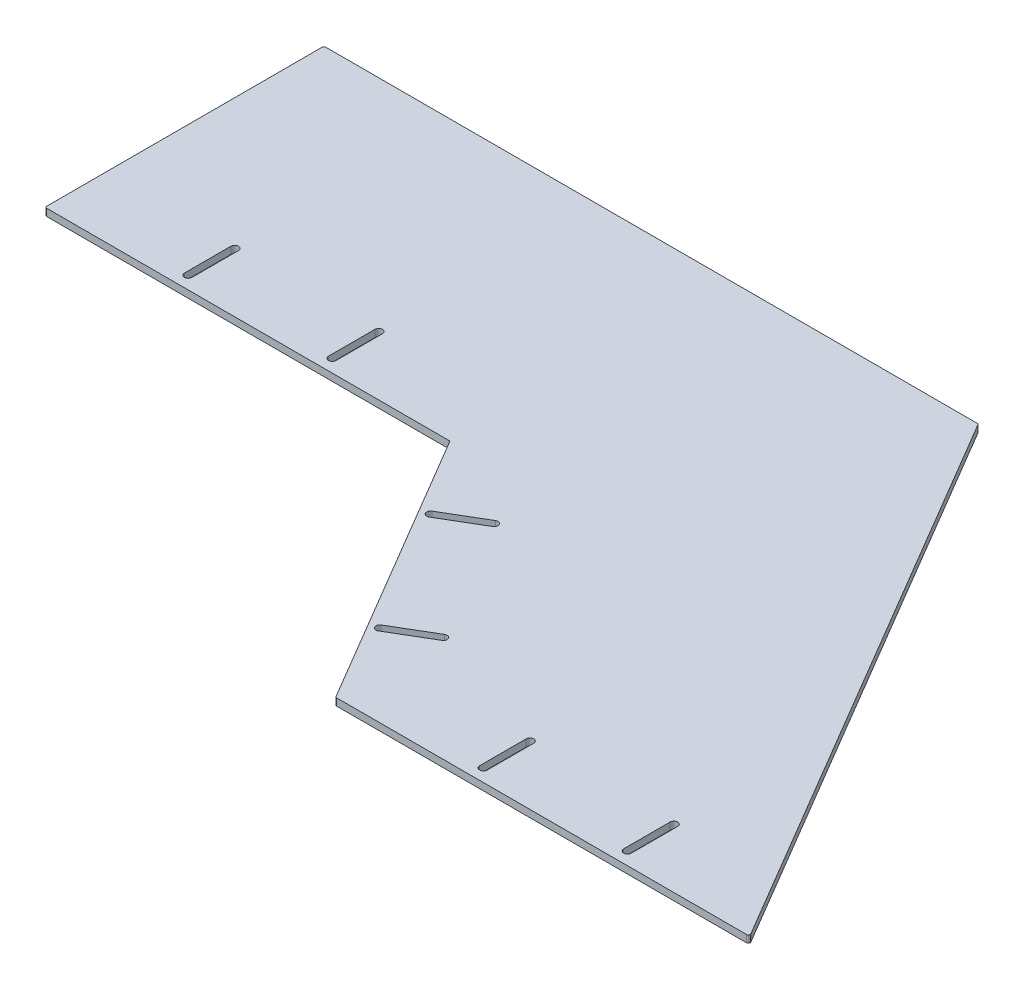
SolidWorks part; units mm, degrees
ref_plane "Front Plane" through (0, 0, 0) normal (1, 0, 0) x (0, 1, 0)
ref_plane "Top Plane" through (0, 0, 0) normal (0, 0, 1) x (0, 1, 0)
ref_plane "Right Plane" through (0, 0, 0) normal (0, 1, 0) x (-1, 0, 0)
sketch "Sketch1" plane through (0, 0, 0) normal (0, 1, 0) x (-1, 0, 0)
  line L0 (0, 0) -> (-183.0301, 310)
  line L1 (-183.0301, 310) -> (46.9699, 310)
  line L2 (46.9699, 310) -> (138.485, 155)
  line L3 (138.485, 155) -> (363.485, 155)
  line L4 (363.485, 155) -> (363.485, 0)
  line L5 (363.485, 0) -> (0, 0)
  line L6 (-108.0301, 302.9) -> (-108.0301, 277.1) construction
  line L7 (-105.9301, 302.9) -> (-105.9301, 277.1)
  line L8 (-110.1301, 302.9) -> (-110.1301, 277.1)
  line L9 (-68.0301, 310) -> (-68.0301, 296.3589) construction
  line L10 (-28.0301, 302.9) -> (-28.0301, 277.1) construction
  line L11 (-30.1301, 302.9) -> (-30.1301, 277.1)
  line L12 (-25.9301, 302.9) -> (-25.9301, 277.1)
  line L13 (45.8686, 251.2852) -> (68.0852, 264.4024) construction
  line L14 (44.8009, 253.0935) -> (67.0176, 266.2107)
  line L15 (46.9362, 249.4769) -> (69.1529, 262.594)
  line L16 (92.7275, 232.5) -> (68.0021, 217.9017) construction
  line L17 (86.5419, 182.3963) -> (108.7586, 195.5135) construction
  line L18 (87.6096, 180.588) -> (109.8263, 193.7051)
  line L19 (85.4742, 184.2047) -> (107.6909, 197.3218)
  line L20 (210.985, 147.9) -> (210.985, 122.1) construction
  line L21 (208.885, 147.9) -> (208.885, 122.1)
  line L22 (213.085, 147.9) -> (213.085, 122.1)
  line L23 (250.985, 155) -> (250.985, 117.5651) construction
  line L24 (290.985, 147.9) -> (290.985, 122.1) construction
  line L25 (293.085, 147.9) -> (293.085, 122.1)
  line L26 (288.885, 147.9) -> (288.885, 122.1)
  arc A0 (-105.9301, 302.9) -> (-110.1301, 302.9) centre (-108.0301, 302.9) ccw
  arc A1 (-110.1301, 277.1) -> (-105.9301, 277.1) centre (-108.0301, 277.1) ccw
  arc A2 (-30.1301, 302.9) -> (-25.9301, 302.9) centre (-28.0301, 302.9) cw
  arc A3 (-25.9301, 277.1) -> (-30.1301, 277.1) centre (-28.0301, 277.1) cw
  arc A4 (44.8009, 253.0935) -> (46.9362, 249.4769) centre (45.8686, 251.2852) ccw
  arc A5 (69.1529, 262.594) -> (67.0176, 266.2107) centre (68.0852, 264.4024) ccw
  arc A6 (87.6096, 180.588) -> (85.4742, 184.2047) centre (86.5419, 182.3963) cw
  arc A7 (107.6909, 197.3218) -> (109.8263, 193.7051) centre (108.7586, 195.5135) cw
  arc A8 (208.885, 147.9) -> (213.085, 147.9) centre (210.985, 147.9) cw
  arc A9 (213.085, 122.1) -> (208.885, 122.1) centre (210.985, 122.1) cw
  arc A10 (293.085, 147.9) -> (288.885, 147.9) centre (290.985, 147.9) ccw
  arc A11 (288.885, 122.1) -> (293.085, 122.1) centre (290.985, 122.1) ccw
  point P6 (-108.0301, 290)
  point P18 (-28.0301, 290)
  point P23 (56.9769, 257.8438)
  point P34 (97.6502, 188.9549)
  point P41 (210.985, 135)
  point P50 (290.985, 135)
  dimension "D7" = 30
  dimension "D9" = 5
  dimension "D11" = 30
  dimension "D13" = 5
  dimension "D15" = 5
  dimension "D1" = 310
  dimension "D2" = 230
  dimension "D3" = 155
  dimension "D4" = 225
  dimension "D5" = 90
  dimension "D6" = 180
  dimension "D8" = 4.2
  dimension "D10" = 40
  dimension "D12" = 4.2
  dimension "D14" = 40
  dimension "D16" = 40
extrude "Boss-Extrude1" add sketch "Sketch1" along normal blind 4 contours L5 L4 L3 L2 L1 L0 A11 L26 A10 L25 A5 L15 A4 L14 A1 L8 A0 L7 L12 A3 L11 A2 L19 A7 L18 A6 L22 A9 L21 A8
fillet "Fillet1" radius 1 6 edges at (0, 2, 0) (183.0301, 2, 310) (-46.9699, 2, 310) (-363.485, 2, 0) (-363.485, 2, 155) (-138.485, 2, 155)
